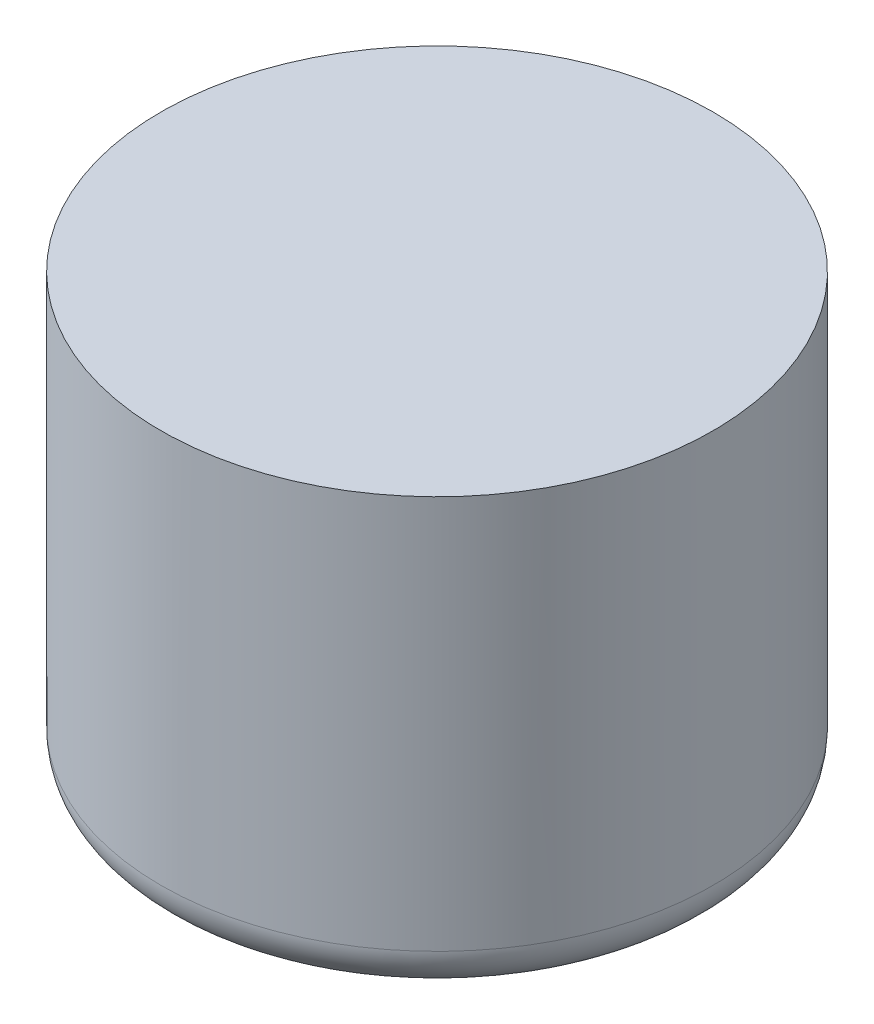
SolidWorks part; units mm, degrees
ref_plane "Front Plane" through (0, 0, 0) normal (0, 0, 1) x (1, 0, 0)
ref_plane "Top Plane" through (0, 0, 0) normal (0, 1, 0) x (1, 0, 0)
ref_plane "Right Plane" through (0, 0, 0) normal (1, 0, 0) x (0, 0, -1)
sketch "Sketch1" plane through (0, 0, 0) normal (0, 1, 0) x (1, 0, 0)
  circle A0 centre (0, 0) radius 31.4999
  dimension "D1" = 62.9999
extrude "Boss-Extrude1" add sketch "Sketch1" along normal blind 49.9999 contours A0
sketch "Sketch2" plane through (0, 49.9999, 0) normal (0, 1, 0) x (1, 0, 0)
  circle A0 centre (0, 0) radius 5.4674
  dimension "D1" = 10.9347
fillet "Fillet1" radius 5.08 1 edges at (0, 0, 31.4999)
ref_plane "Plane1" through (0, 0, 100) normal (0, 0, 1) x (1, 0, 0)
sketch "Sketch3" plane through (0, 0, 100) normal (0, 0, 1) x (1, 0, 0)
  line L0 (-31.4999, 49.9999) -> (-31.4999, 5.08) construction
  line L2 (-74.7116, 27.54) -> (74.7116, 27.54) construction
  line L3 (0, 27.54) -> (0, 0) construction
  line L4 (31.4999, 5.08) -> (-31.4999, 5.08) construction
  text T0 "ECO PUCK" font "Adobe Gothic Std B" height in points 24
  point P10 (-31.4999, 27.54)
  dimension "D1" = 149.4233
